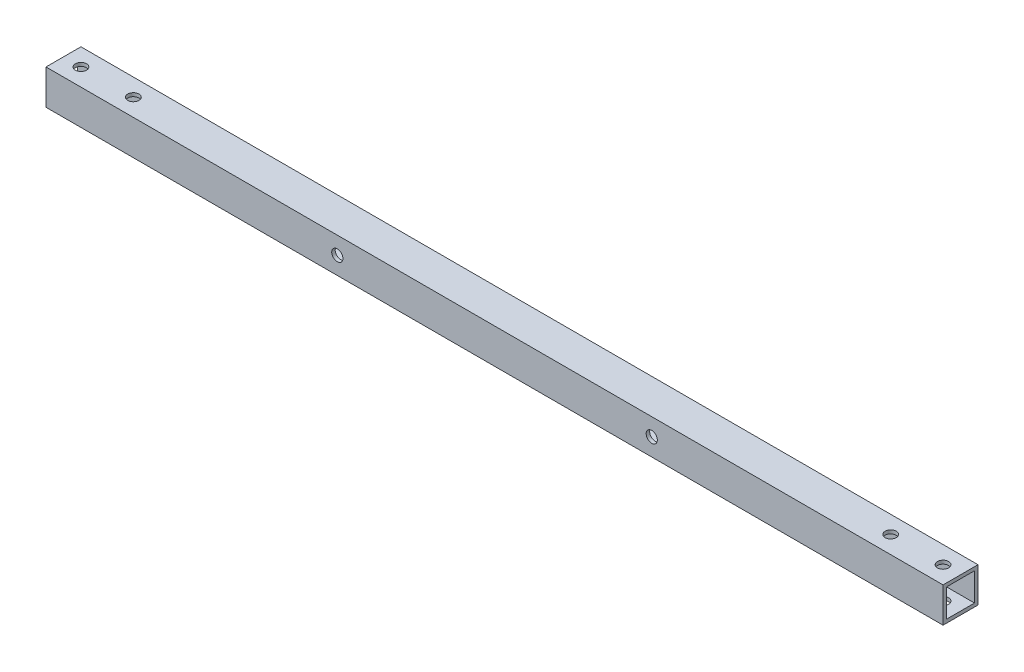
SolidWorks part; units mm, degrees
material "5052-O"
ref_plane "正面" through (0, 0, 0) normal (0, 0, 1) x (1, 0, 0)
ref_plane "平面" through (0, 0, 0) normal (0, 1, 0) x (1, 0, 0)
ref_plane "右側面" through (0, 0, 0) normal (1, 0, 0) x (0, 0, -1)
sketch "ｽｹｯﾁ1" plane through (0, 0, 0) normal (1, 0, 0) x (0, 0, -1)
  line L1 (-5, 5) -> (5, 5)
  line L2 (-5, 5) -> (-5, -5)
  line L3 (-5, -5) -> (5, -5)
  line L4 (5, 5) -> (5, -5)
  line L5 (-5, 5) -> (5, -5) construction
  line L6 (-5, -5) -> (5, 5) construction
  point P0 (0, 0)
  dimension "D1" = 10
  dimension "D2" = 10
extrude "ﾎﾞｽ - 押し出し1" add sketch "ｽｹｯﾁ1" along normal mid plane 256.7261
sketch "ｽｹｯﾁ2" plane through (128.363, 0, 0) normal (1, 0, 0) x (0, 0, -1)
  line L0 (5, 5) -> (-5, 5) construction
  line L1 (-4, 4) -> (4, 4)
  line L2 (-4, 4) -> (-4, -4)
  line L3 (-4, -4) -> (4, -4)
  line L4 (4, 4) -> (4, -4)
  line L5 (-4, 4) -> (4, -4) construction
  line L6 (-4, -4) -> (4, 4) construction
  line L7 (5, -5) -> (5, 5) construction
  point P0 (0, 0)
  dimension "D1" = 1
  dimension "D2" = 1
extrude "ｶｯﾄ - 押し出し1" cut sketch "ｽｹｯﾁ2" against normal through all
sketch "ｽｹｯﾁ3" plane through (0, 5, 0) normal (0, 1, 0) x (1, 0, 0)
  line L0 (128.363, 5) -> (-128.363, 5) construction
  line L1 (-128.363, 5) -> (-128.363, -5) construction
  line L2 (0, -5.5) -> (0, 5.5) construction
  circle A0 centre (-123.363, 0) radius 1.6
  circle A1 centre (-108.363, 0) radius 1.6
  circle A2 centre (108.363, 0) radius 1.6
  circle A3 centre (123.363, 0) radius 1.6
  dimension "D1" = 3.2
  dimension "D2" = 5
  dimension "D3" = 5
  dimension "D4" = 2
extrude "ｶｯﾄ - 押し出し2" cut sketch "ｽｹｯﾁ3" against normal through all
sketch "ｽｹｯﾁ4" plane through (0, 0, 5) normal (0, 0, 1) x (1, 0, 0)
  line L0 (128.363, 5) -> (-128.363, 5) construction
  line L1 (0, -5.5) -> (0, 5.5) construction
  circle A0 centre (-45, 0) radius 1.6
  circle A1 centre (45, 0) radius 1.6
  dimension "D1" = 3.2
  dimension "D2" = 5
  dimension "D3" = 45
extrude "ｶｯﾄ - 押し出し3" cut sketch "ｽｹｯﾁ4" against normal through all
